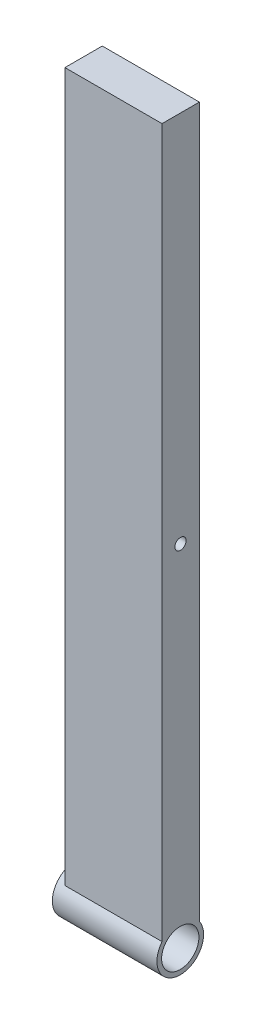
SolidWorks part; units mm, degrees
material "1060-H18 Rod (SS)"
ref_plane "Front Plane" through (0, 0, 0) normal (0, 0, 1) x (1, 0, 0)
ref_plane "Top Plane" through (0, 0, 0) normal (0, 1, 0) x (1, 0, 0)
ref_plane "Right Plane" through (0, 0, 0) normal (1, 0, 0) x (0, 0, -1)
sketch "Sketch8" plane through (0, 0, 0) normal (0, 1, 0) x (1, 0, 0)
  line L1 (13, -5) -> (-13, -5)
  line L2 (13, -5) -> (13, 5)
  line L3 (13, 5) -> (-13, 5)
  line L4 (-13, -5) -> (-13, 5)
  line L5 (13, -5) -> (-13, 5) construction
  line L6 (13, 5) -> (-13, -5) construction
  point P0 (0, 0)
  dimension "D1" = 10
  dimension "D2" = 26
extrude "Boss-Extrude5" add sketch "Sketch8" along normal blind 190
sketch "Sketch9" plane through (13, 0, 0) normal (1, 0, 0) x (0, 0, -1)
  circle A0 centre (-0.1184, -3.5868) radius 6.25
  dimension "D1" = 12.5
extrude "Boss-Extrude7" add sketch "Sketch9" against normal blind 28 contours A0
sketch "Sketch13" plane through (13, 0, 0) normal (1, 0, 0) x (0, 0, -1)
  line L3 (-6.3684, -3.5868) -> (-0.1184, -3.5868) construction
  arc A0 (-5, 0.3161) -> (5, 0) centre (-0.1184, -3.5868) ccw construction
  circle A1 centre (-0.1184, -3.5868) radius 5
  dimension "D1" = 10
extrude "Cut-Extrude3" cut sketch "Sketch13" against normal blind 28
sketch "Sketch14" plane through (13, 0, 0) normal (1, 0, 0) x (0, 0, -1)
  line L0 (-0.1184, -9.8368) -> (0, 190) construction
  line L1 (-5, 190) -> (5, 190) construction
  arc A0 (-5, 0.3161) -> (5, 0) centre (-0.1184, -3.5868) ccw construction
  circle A1 centre (-0.0592, 90.0816) radius 1.5
  dimension "D1" = 3
extrude "Cut-Extrude4" cut sketch "Sketch14" against normal blind 28
